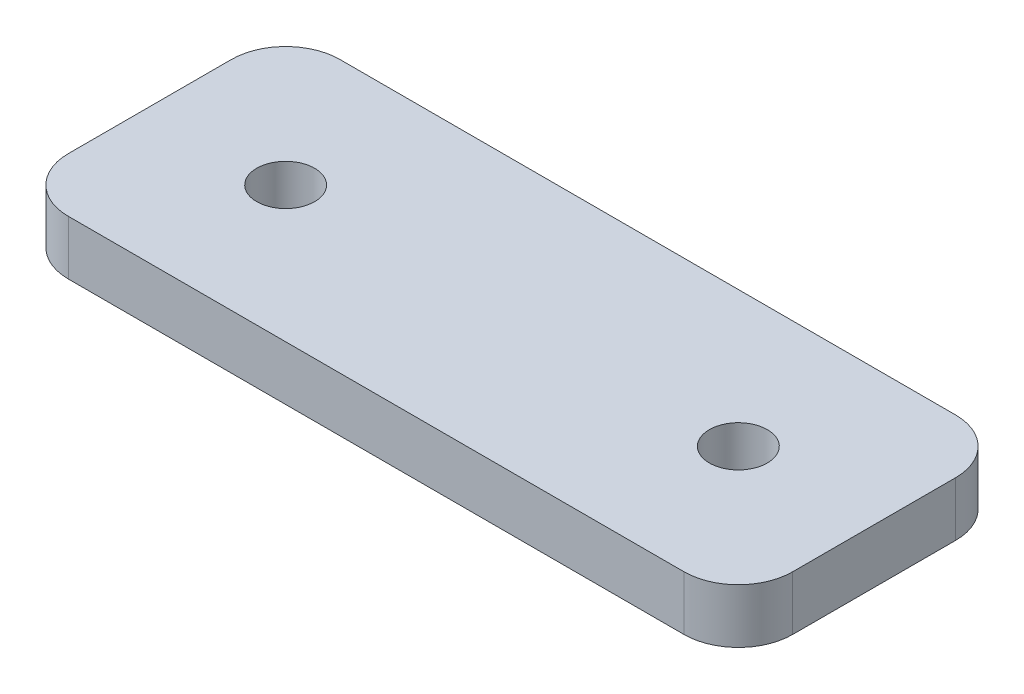
SolidWorks part; units mm, degrees
material "ABS"
ref_plane "前视基准面" through (0, 0, 0) normal (0, 0, 1) x (1, 0, 0)
ref_plane "上视基准面" through (0, 0, 0) normal (0, 1, 0) x (1, 0, 0)
ref_plane "右视基准面" through (0, 0, 0) normal (1, 0, 0) x (0, 0, -1)
other "Configuration Table"
sketch "草图1" plane through (0, 0, 0) normal (0, 1, 0) x (1, 0, 0)
  line L0 (-28.3912, 0) -> (34.5899, 0) construction
  line L1 (-20, -7.5) -> (20, -7.5)
  line L2 (-20, -7.5) -> (-20, 7.5)
  line L3 (-20, 7.5) -> (20, 7.5)
  line L4 (20, -7.5) -> (20, 7.5)
  line L5 (-20, -7.5) -> (20, 7.5) construction
  line L6 (-20, 7.5) -> (20, -7.5) construction
  line L7 (0, 18.8565) -> (0, -12.9416) construction
  circle A0 centre (-12.5, 0) radius 1.6
  circle A2 centre (12.5, 0) radius 1.6
  point P0 (0, 0)
  dimension "D3" = 3.2
  dimension "D4" = 25
  dimension "D1" = 15
  dimension "D2" = 40
extrude "凸台-拉伸1" add sketch "草图1" along normal blind 3
fillet "圆角1" radius 3 4 edges at (-20, 1.5, 7.5) (-20, 1.5, -7.5) (20, 1.5, -7.5) (20, 1.5, 7.5)
